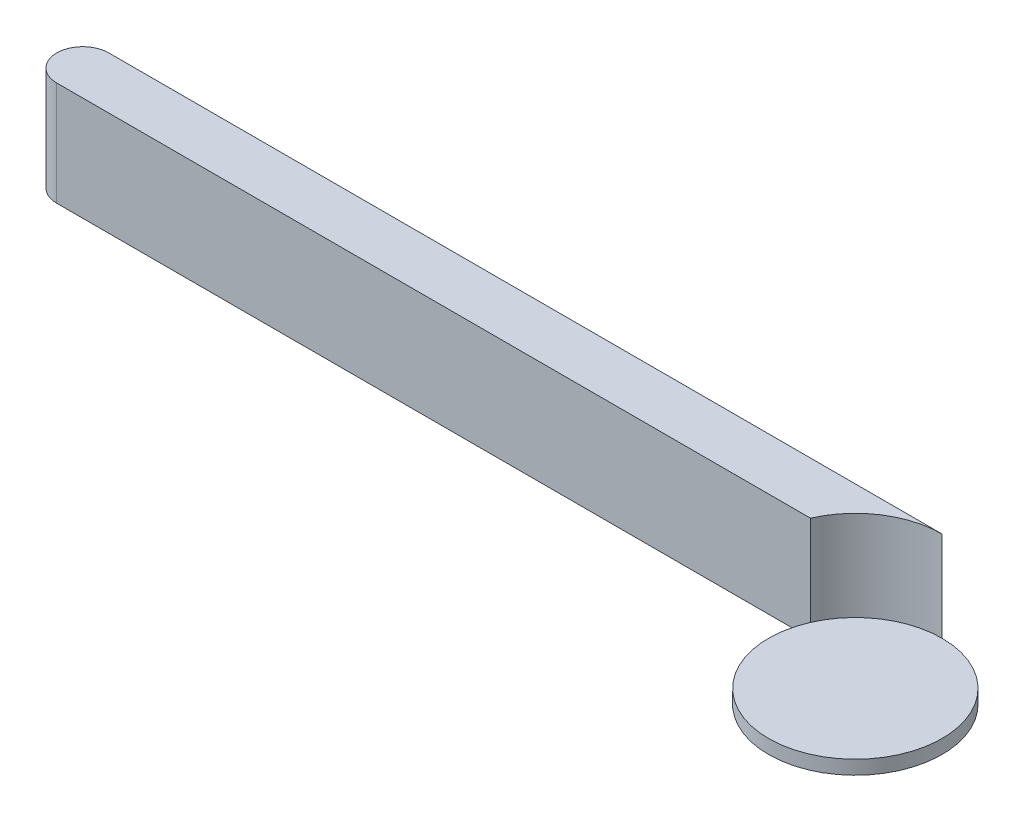
SolidWorks part; units mm, degrees
ref_plane "Front Plane" through (0, 0, 0) normal (0, 0, 1) x (1, 0, 0)
ref_plane "Top Plane" through (0, 0, 0) normal (0, 1, 0) x (1, 0, 0)
ref_plane "Right Plane" through (0, 0, 0) normal (1, 0, 0) x (0, 0, -1)
sketch "Sketch1" plane through (0, 0, 0) normal (0, 1, 0) x (1, 0, 0)
  line L1 (0, -4.7625) -> (137.8503, -4.7625)
  line L3 (0, 4.7625) -> (152.4, 4.7625)
  arc A0 (0, 4.7625) -> (0, -4.7625) centre (0, 0) ccw
  arc A1 (137.8503, -4.7625) -> (152.4, 4.7625) centre (152.4, -11.1125) ccw
  point P4 (152.4, 6.35)
  point P7 (0, 0)
  point P9 (135.0043, -9.525)
  point P10 (0, 0)
  dimension "D1" = 9.525
  dimension "D3" = 31.75
  dimension "D2" = 152.4
extrude "Boss-Extrude1" add sketch "Sketch1" along normal blind 19.05
sketch "Sketch2" plane through (0, 19.05, 0) normal (0, 1, 0) x (1, 0, 0)
  circle A0 centre (152.4, -11.1125) radius 15.875
extrude "Cut-Extrude1" cut sketch "Sketch2" against normal blind 16.51
